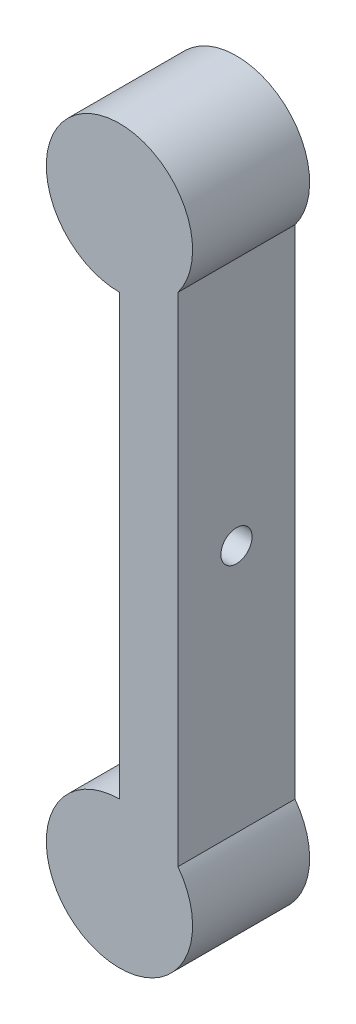
SolidWorks part; units mm, degrees
material "ABS"
ref_plane "Plano frontal" through (0, 0, 0) normal (0, 0, 1) x (1, 0, 0)
ref_plane "Plano superior" through (0, 0, 0) normal (0, 1, 0) x (1, 0, 0)
ref_plane "Plano direito" through (0, 0, 0) normal (1, 0, 0) x (0, 0, -1)
sketch "Esboço1" plane through (0, 0, 0) normal (0, 0, 1) x (1, 0, 0)
  line L0 (6, 55.5) -> (6, 4.5)
  line L1 (0, 60) -> (0, 0) construction
  line L7 (0, 52.5) -> (0, 7.5)
  circle A0 centre (0, 60) radius 4
  circle A1 centre (0, 0) radius 4
  arc A2 (6, 55.5) -> (0, 52.5) centre (0, 60) ccw
  arc A3 (0, 7.5) -> (6, 4.5) centre (0, 0) ccw
  point P14 (-9.5, 38)
  dimension "D1" = 8
  dimension "D2" = 15
  dimension "D3" = 60
  dimension "D4" = 6
  dimension "D5" = 0
extrude "Ressalto-extrusão1" add sketch "Esboço1" along normal blind 10 contours L0 A3 A2
sketch "Esboço3" plane through (0, 0, 10) normal (0, 0, 1) x (1, 0, 0)
  line L2 (0, 52.5) -> (0, 7.5)
  line L4 (6, 55.5) -> (6, 4.5)
  arc A0 (6, 55.5) -> (0, 52.5) centre (0, 60) ccw
  arc A1 (0, 7.5) -> (6, 4.5) centre (0, 0) ccw
extrude "Ressalto-extrusão2" add sketch "Esboço3" along normal blind 2
sketch "Esboço2" plane through (0, 0, 0) normal (-1, 0, 0) x (0, 0, 1)
  line L0 (0, 30) -> (12, 30) construction
  line L1 (0, 52.5) -> (0, 7.5) construction
  line L3 (12, 52.5) -> (12, 7.5) construction
  circle A0 centre (6, 30) radius 1.6
  point P4 (12, 30)
  point P8 (10, 30)
  dimension "D1" = 3.2
extrude "Corte-extrusão1" cut sketch "Esboço2" against normal blind 10 contours A0
